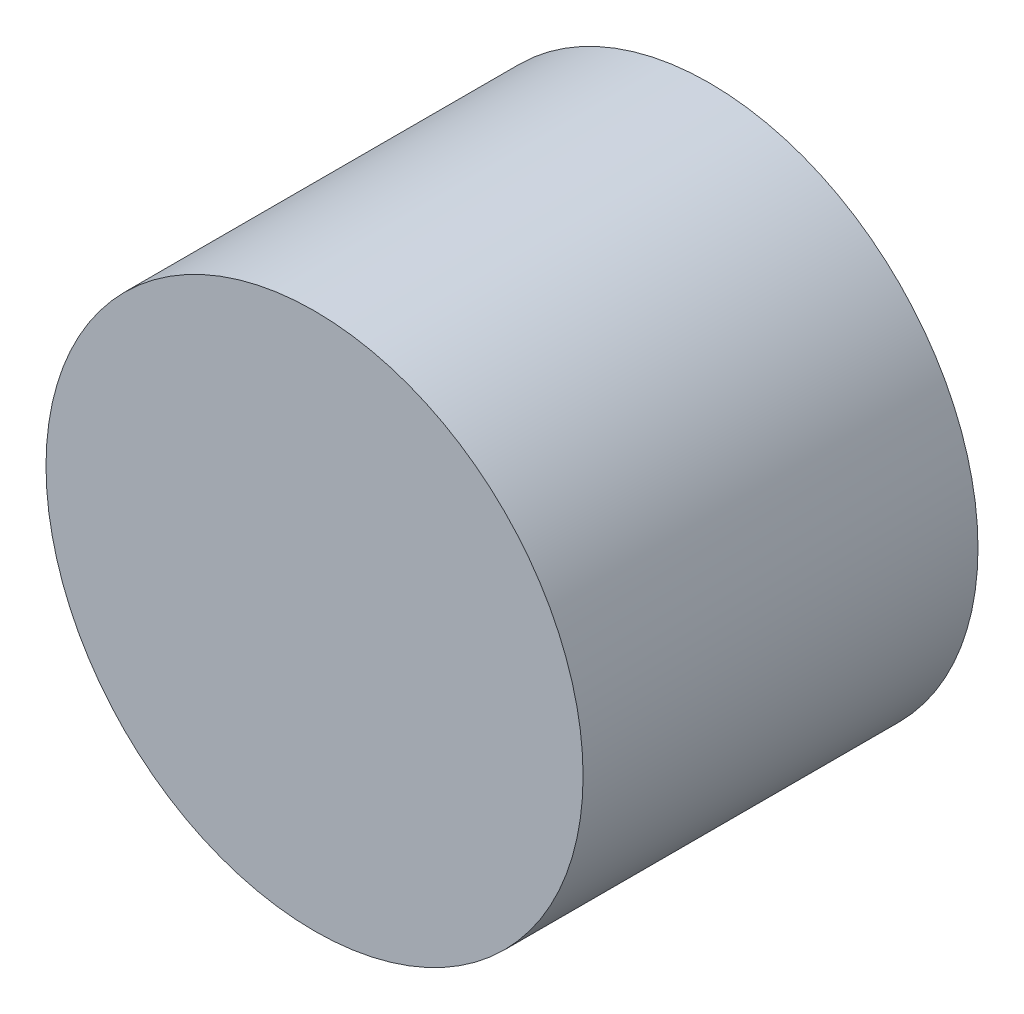
SolidWorks part; units mm, degrees
ref_plane "前视基准面" through (0, 0, 0) normal (0, 0, 1) x (1, 0, 0)
ref_plane "上视基准面" through (0, 0, 0) normal (0, 1, 0) x (1, 0, 0)
ref_plane "右视基准面" through (0, 0, 0) normal (1, 0, 0) x (0, 0, -1)
other "Configuration Table"
sketch "草图1" plane through (0, 0, 0) normal (0, 0, 1) x (1, 0, 0)
  circle A0 centre (0, 0) radius 17
  dimension "D1" = 34
extrude "凸台-拉伸1" add sketch "草图1" along normal blind 25
sketch "草图5" plane through (0, 0, 0) normal (0, 0, -1) x (-1, 0, 0)
  point P0 (0, 0)
hole_wizard "M5 螺纹孔1" positions "草图5" profile "草图4" tap size "M5" standard "GB"
sketch "草图4" plane through (0, 0, 0) normal (1, 0, 0) x (0, 1, 0)
  line L0 (0, 0) -> (0, 5.2618)
  line L1 (0, 5.2618) -> (2.1, 4)
  line L2 (2.1, 4) -> (2.1, 0)
  line L5 (2.1, 0) -> (0, 0)
  line L10 (0, 5.2618) -> (-2.1, 4) construction
  line L11 (0, -6.35) -> (0, 107.95) construction
  dimension "螺纹孔钻头直径" = 4.2
  dimension "螺纹孔钻头深度" = 4
  dimension "导头角度" = 118
cosmetic thread "孔螺纹线1"
